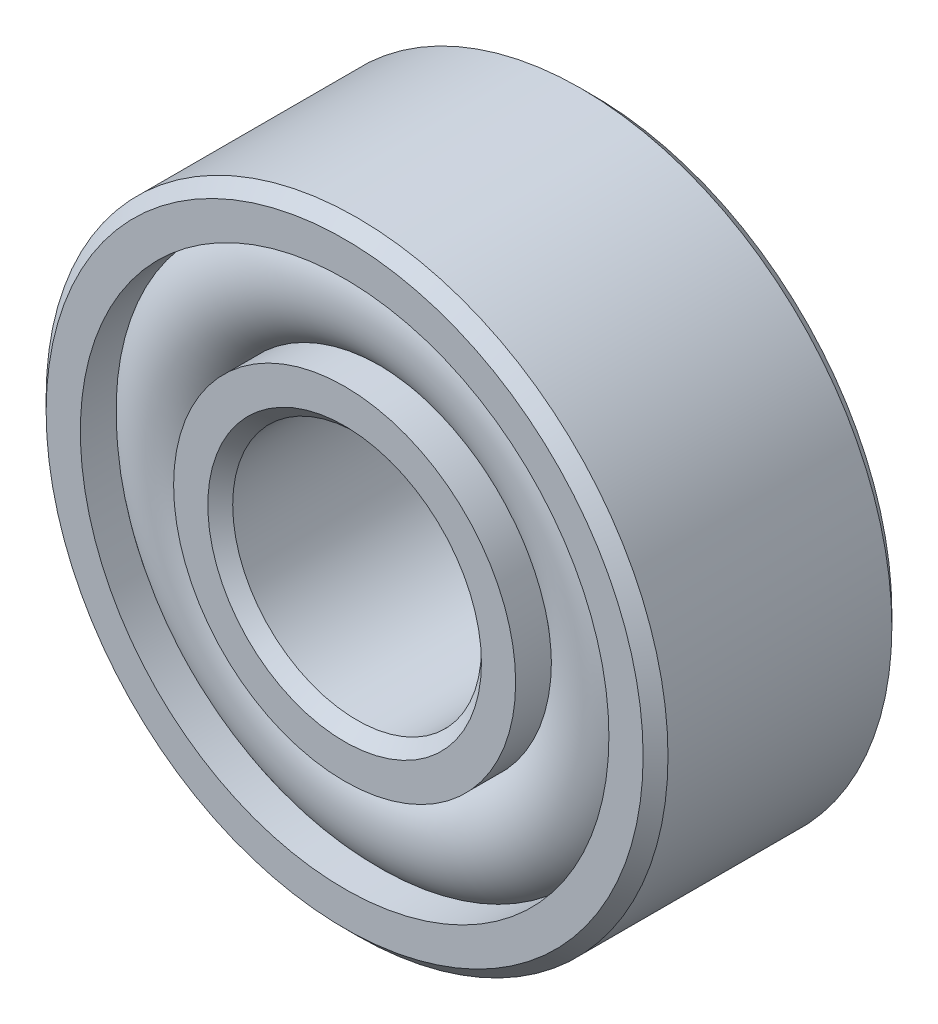
SolidWorks part; units mm, degrees
material "Stainless_Steel_Ruleman"
ref_plane "Front Plane" through (0, 0, 0) normal (0, 0, 1) x (1, 0, 0)
ref_plane "Top Plane" through (0, 0, 0) normal (0, 1, 0) x (1, 0, 0)
ref_plane "Right Plane" through (0, 0, 0) normal (1, 0, 0) x (0, 0, -1)
sketch "Sketch1" plane through (0, 0, 0) normal (0, 1, 0) x (1, 0, 0)
  line L0 (2.75, 3.4248) -> (2.75, 4)
  line L1 (2.75, 4) -> (2, 4)
  line L2 (2, 4) -> (2, 0)
  line L3 (2, 0) -> (2.75, 0)
  line L4 (2.75, 0) -> (2.75, 0.5752)
  line L5 (4.25, 0.5752) -> (4.25, 0)
  line L6 (4.25, 0) -> (5, 0)
  line L7 (5, 0) -> (5, 4)
  line L8 (5, 4) -> (4.25, 4)
  line L9 (4.25, 4) -> (4.25, 3.4248)
  line L10 (0, 4) -> (0, 0) construction
  line L11 (0, 4) -> (2, 4) construction
  line L12 (2, 0) -> (0, 0) construction
  line L13 (3.5, 4) -> (3.5, 3.75) construction
  line L14 (0, 2) -> (5, 2) construction
  line L15 (2.75, 4) -> (4.25, 4) construction
  arc A0 (4.25, 0.5752) -> (2.75, 0.5752) centre (3.5, 1.2775) cw
  arc A1 (4.25, 3.4248) -> (2.75, 3.4248) centre (3.5, 2.7225) ccw
  dimension "D6" = 0.25
  dimension "D1" = 4
  dimension "D2" = 2
  dimension "D3" = 0.75
  dimension "D4" = 5
  dimension "D5" = 0.75
revolve "Revolve1" add sketch "Sketch1" angle 360 about L10
chamfer "Chamfer1" distance 0.2 angle 45 1 edges at (5, 0, -4)
chamfer "Chamfer2" distance 0.2 angle 45 1 edges at (2, 0, -4)
chamfer "Chamfer3" distance 0.2 angle 45 1 edges at (5, 0, 0)
chamfer "Chamfer4" distance 0.2 angle 45 1 edges at (2, 0, 0)
